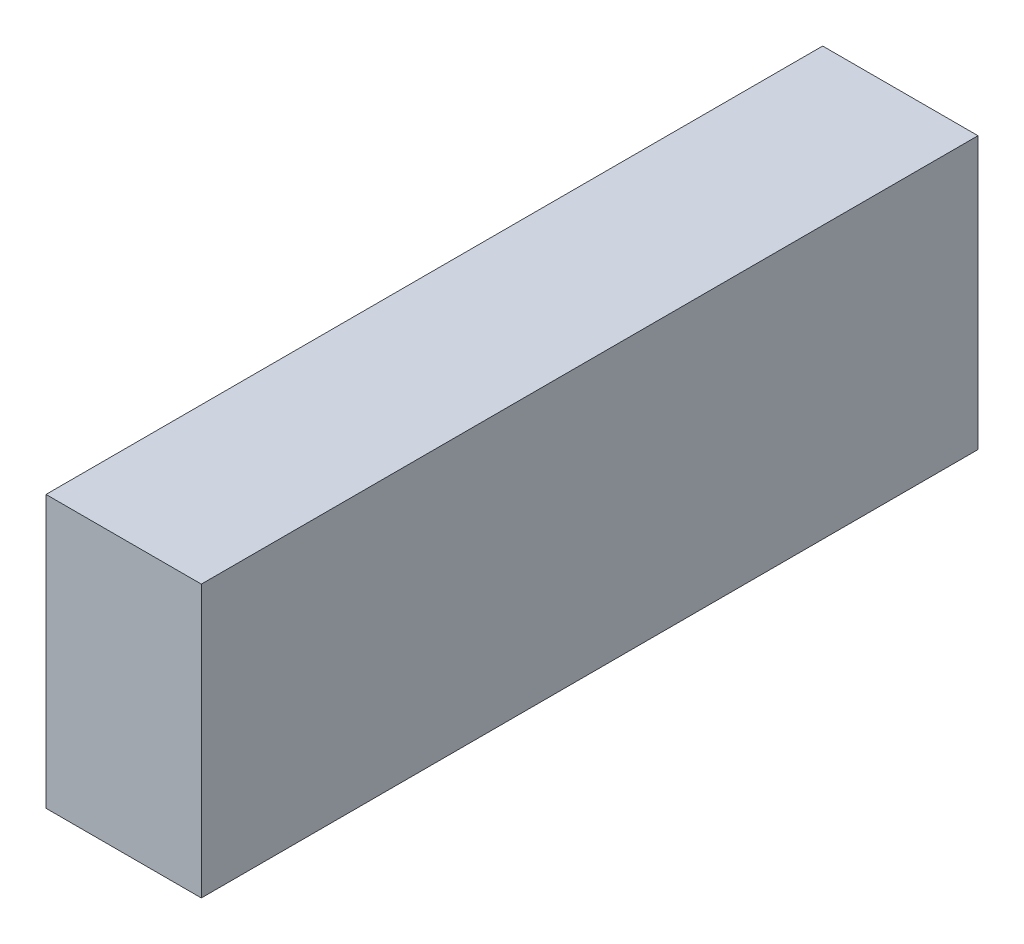
SolidWorks part; units mm, degrees
ref_plane "Ebene vorne" through (0, 0, 0) normal (0, 0, 1) x (1, 0, 0)
ref_plane "Ebene oben" through (0, 0, 0) normal (0, 1, 0) x (1, 0, 0)
ref_plane "Ebene rechts" through (0, 0, 0) normal (1, 0, 0) x (0, 0, -1)
sketch "Skizze1" plane through (0, 0, 0) normal (1, 0, 0) x (0, 0, -1)
  line L1 (50, -17.5) -> (-50, -17.5)
  line L2 (50, -17.5) -> (50, 17.5)
  line L3 (50, 17.5) -> (-50, 17.5)
  line L4 (-50, -17.5) -> (-50, 17.5)
  line L5 (50, -17.5) -> (-50, 17.5) construction
  line L6 (50, 17.5) -> (-50, -17.5) construction
  point P0 (0, 0)
  dimension "D1" = 35
  dimension "D2" = 100
extrude "Aufsatz-Linear austragen1" add sketch "Skizze1" along normal blind 20
